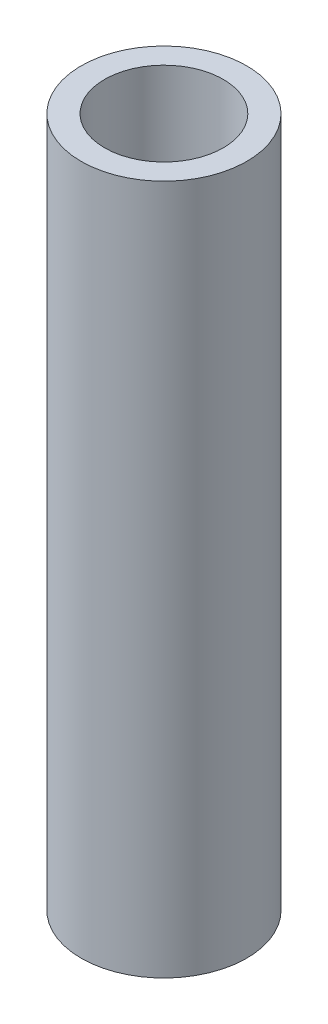
SolidWorks part; units mm, degrees
ref_plane "Front Plane" through (0, 0, 0) normal (0, 0, 1) x (1, 0, 0)
ref_plane "Top Plane" through (0, 0, 0) normal (0, 1, 0) x (1, 0, 0)
ref_plane "Right Plane" through (0, 0, 0) normal (1, 0, 0) x (0, 0, -1)
sketch "Sketch1" plane through (0, 0, 0) normal (0, 1, 0) x (1, 0, 0)
  circle A0 centre (0, 0) radius 7.6454
  circle A1 centre (0, 0) radius 10.668
  dimension "D1" = 21.336
  dimension "D2" = 15.2908
extrude "Boss-Extrude1" add sketch "Sketch1" along normal blind 88.9
